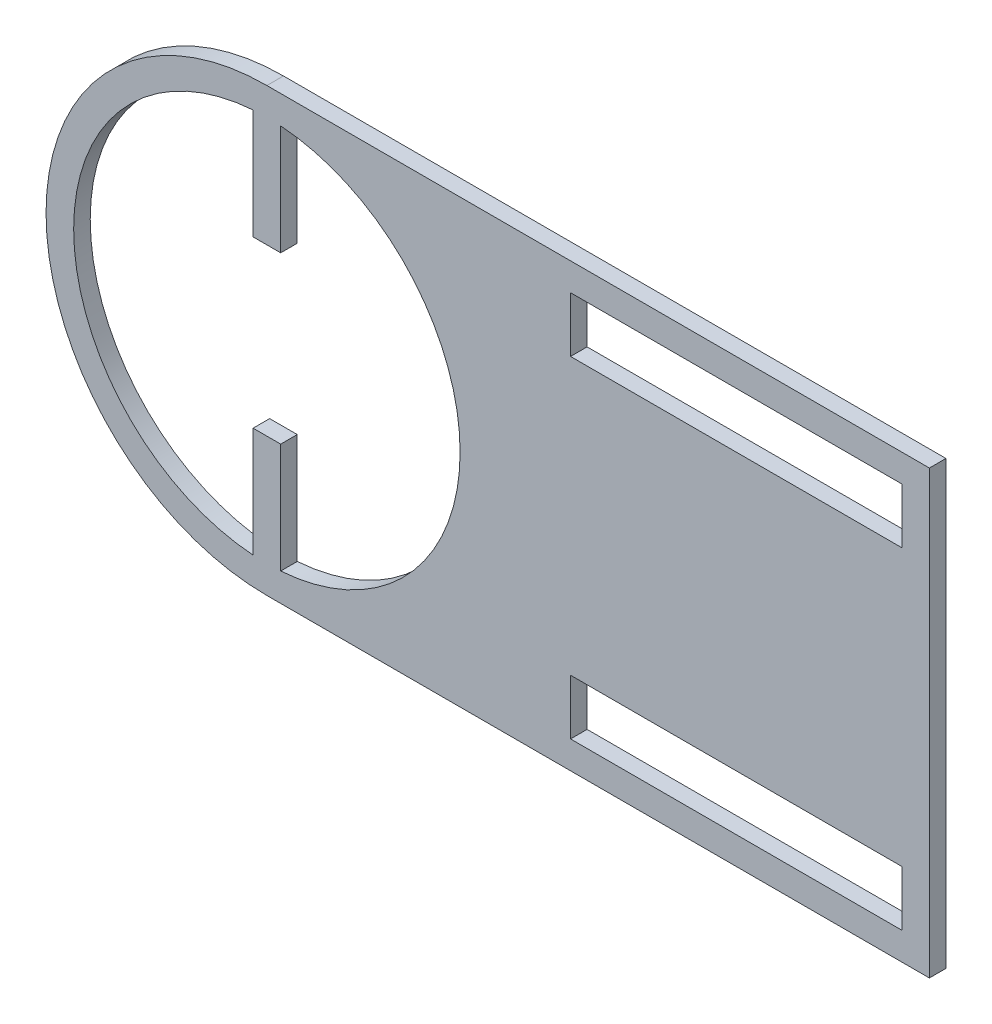
SolidWorks part; units mm, degrees
material "Hexcel AS4C (3000 Filaments)"
ref_plane "Front Plane" through (0, 0, 0) normal (0, 0, 1) x (1, 0, 0)
ref_plane "Top Plane" through (0, 0, 0) normal (0, 1, 0) x (1, 0, 0)
ref_plane "Right Plane" through (0, 0, 0) normal (1, 0, 0) x (0, 0, -1)
sketch "Sketch1" plane through (0, 0, 0) normal (0, 0, 1) x (1, 0, 0)
  line L1 (0, 0) -> (120, 0)
  line L3 (0, 80) -> (120, 80)
  line L4 (120, 0) -> (120, 80)
  line L5 (115, 65) -> (55, 65)
  line L6 (115, 65) -> (115, 75)
  line L7 (115, 75) -> (55, 75)
  line L8 (55, 65) -> (55, 75)
  line L9 (115, 5) -> (55, 5)
  line L10 (115, 5) -> (115, 15)
  line L11 (115, 15) -> (55, 15)
  line L12 (55, 5) -> (55, 15)
  line L13 (2.5, 55) -> (2.5, 74.9106)
  line L15 (2.5, 5.0894) -> (2.5, 25)
  line L17 (-2.5, 5.0894) -> (-2.5, 25)
  line L20 (2.5, 25) -> (-2.5, 25)
  line L24 (2.5, 55) -> (-2.5, 55)
  line L26 (-2.5, 55) -> (-2.5, 74.9106)
  arc A1 (2.5, 5.0894) -> (2.5, 74.9106) centre (0, 40) ccw
  arc A2 (0, 80) -> (0, 0) centre (0, 40) ccw
  arc A3 (-2.5, 74.9106) -> (-2.5, 5.0894) centre (0, 40) ccw
  dimension "D3" = 0
  dimension "D11" = 70
  dimension "D1" = 120
  dimension "D2" = 80
  dimension "D4" = 60
  dimension "D5" = 5
  dimension "D6" = 5
  dimension "D7" = 10
  dimension "D8" = 10
  dimension "D9" = 5
  dimension "D10" = 5
  dimension "D12" = 2.5
  dimension "D13" = 30
extrude "Boss-Extrude1" add sketch "Sketch1" along normal blind 3
